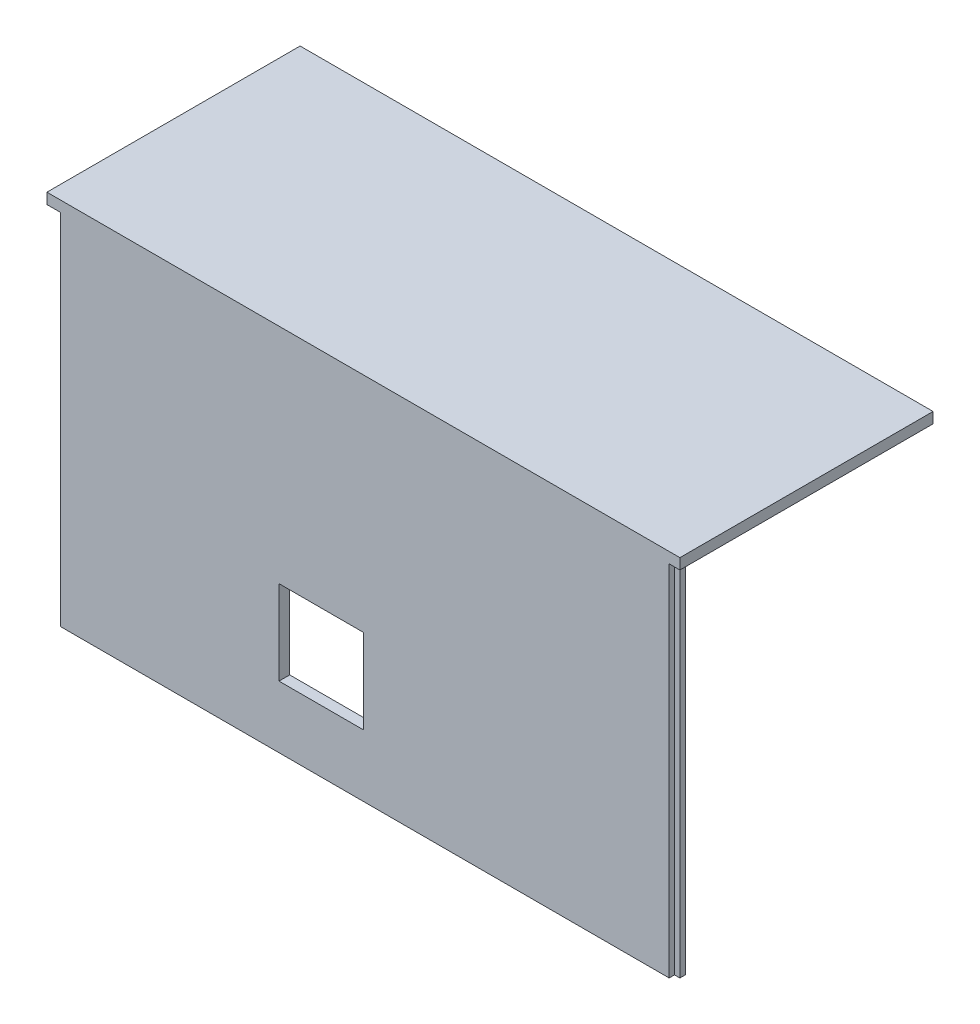
SolidWorks part; units mm, degrees
ref_plane "Front Plane" through (0, 0, 0) normal (0, 0, 1) x (1, 0, 0)
ref_plane "Top Plane" through (0, 0, 0) normal (0, 1, 0) x (1, 0, 0)
ref_plane "Right Plane" through (0, 0, 0) normal (1, 0, 0) x (0, 0, -1)
sketch "Sketch1" plane through (0, 0, 0) normal (0, 0, 1) x (1, 0, 0)
  line L1 (-72.842, 47.1418) -> (77.158, 47.1418)
  line L2 (-72.842, 47.1418) -> (-72.842, -37.8582)
  line L3 (-72.842, -37.8582) -> (77.158, -37.8582)
  line L4 (77.158, 47.1418) -> (77.158, -37.8582)
  dimension "D1" = 150
  dimension "D2" = 85
extrude "Boss-Extrude1" add sketch "Sketch1" along normal blind 2.54
sketch "Sketch2" plane through (0, 0, 0) normal (0, 0, -1) x (-1, 0, 0)
  line L0 (72.842, -37.8582) -> (-77.158, -37.8582) construction
  line L1 (17.842, -23.1582) -> (-2.158, -23.1582)
  line L2 (17.842, -23.1582) -> (17.842, -3.1582)
  line L3 (17.842, -3.1582) -> (-2.158, -3.1582)
  line L4 (-2.158, -23.1582) -> (-2.158, -3.1582)
  line L5 (17.842, -23.1582) -> (-2.158, -3.1582) construction
  line L6 (17.842, -3.1582) -> (-2.158, -23.1582) construction
  line L7 (-77.158, -37.8582) -> (-77.158, 47.1418) construction
  point P0 (7.842, -13.1582)
  dimension "D4" = 75
  dimension "D1" = 14.7
  dimension "D2" = 20
  dimension "D3" = 20
extrude "Cut-Extrude1" cut sketch "Sketch2" against normal blind 2.54
sketch "Sketch3" plane through (0, 0, 0) normal (0, 0, -1) x (-1, 0, 0)
  line L0 (72.842, -37.8582) -> (-77.158, -37.8582) construction
  line L1 (-77.158, -37.8582) -> (-77.158, 47.1418) construction
  circle A0 centre (-51.158, -21.8582) radius 3
  circle A1 centre (-16.158, -21.8582) radius 3
  point P9 (-16.158, -21.8582)
  dimension "D1" = 6
  dimension "D3" = 16
  dimension "D4" = 26
  dimension "D2" = 2
extrude "Boss-Extrude2" add sketch "Sketch3" along normal blind 8
sketch "Sketch9" plane through (0, 0, -8) normal (0, 0, -1) x (-1, 0, 0)
  circle A0 centre (-51.158, -21.8582) radius 0.5
  circle A1 centre (-16.158, -21.8582) radius 0.5
  dimension "D1" = 1
  dimension "D2" = 2
extrude "Cut-Extrude7" cut sketch "Sketch9" against normal blind 4
sketch "Sketch10" plane through (0, 47.1418, 0) normal (0, 1, 0) x (1, 0, 0)
  line L0 (77.158, 0) -> (-72.842, 0) construction
  line L2 (-69.667, -1.27) -> (-69.667, -2.54)
  line L3 (-69.667, -2.54) -> (-72.842, -2.54)
  line L4 (-72.842, 0) -> (-72.842, -2.54)
  line L5 (-72.842, 0) -> (-70.937, 0)
  line L6 (-70.937, 0) -> (-70.937, -1.27)
  line L7 (-70.937, -1.27) -> (-69.667, -1.27)
  line L9 (75.888, 0) -> (75.888, -1.27)
  line L10 (77.158, 0) -> (75.888, 0)
  line L11 (77.158, 0) -> (77.158, -2.54)
  line L12 (74.618, -2.54) -> (77.158, -2.54)
  line L13 (74.618, -1.27) -> (74.618, -2.54)
  line L14 (75.888, -1.27) -> (74.618, -1.27)
  dimension "D1" = 1.27
  dimension "D2" = 3.175
  dimension "D3" = 1.905
extrude "Cut-Extrude8" cut sketch "Sketch10" against normal blind 85
sketch "Sketch11" plane through (0, 47.1418, 0) normal (0, 1, 0) x (1, 0, 0)
  line L9 (-72.842, -2.54) -> (77.158, -2.54)
  line L10 (-72.842, -2.54) -> (-72.842, 57.46)
  line L11 (-72.842, 57.46) -> (77.158, 57.46)
  line L12 (77.158, -2.54) -> (77.158, 57.46)
  point P0 (-69.667, -2.54)
  point P2 (-70.937, -1.27)
  point P3 (-71.572, -2.54)
  dimension "D1" = 150
  dimension "D2" = 60
extrude "Boss-Extrude3" add sketch "Sketch11" along normal blind 2.54
